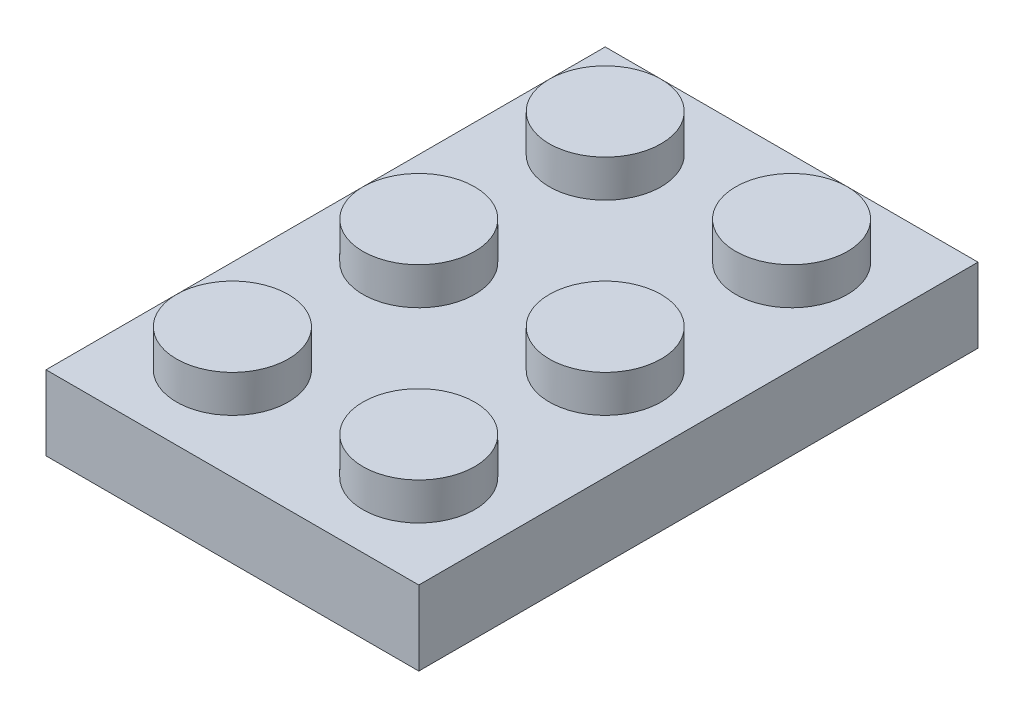
SolidWorks part; units mm, degrees
ref_plane "Front Plane" through (0, 0, 0) normal (0, 0, 1) x (1, 0, 0)
ref_plane "Top Plane" through (0, 0, 0) normal (0, 1, 0) x (1, 0, 0)
ref_plane "Right Plane" through (0, 0, 0) normal (1, 0, 0) x (0, 0, -1)
sketch "Sketch1" plane through (0, 0, 0) normal (0, 1, 0) x (1, 0, 0)
  line L1 (0, 0) -> (16, 0)
  line L2 (0, 0) -> (0, 24)
  line L3 (0, 24) -> (16, 24)
  line L4 (16, 0) -> (16, 24)
  dimension "D1" = 16
  dimension "D2" = 24
extrude "Boss-Extrude1" add sketch "Sketch1" along normal blind 3.2
sketch "Sketch2" plane through (0, 3.2, 0) normal (0, 1, 0) x (1, 0, 0)
  line L0 (8, 0) -> (8, 24) construction
  line L1 (0, 0) -> (16, 0) construction
  line L2 (16, 24) -> (0, 24) construction
  line L3 (16, 0) -> (16, 4) construction
  line L4 (16, 0) -> (16, 24) construction
  line L5 (16, 4) -> (12, 4) construction
  circle A0 centre (12, 4) radius 2.4
  dimension "D3" = 4.8
  dimension "D1" = 4
  dimension "D2" = 4
extrude "Boss-Extrude2" add sketch "Sketch2" along normal blind 1.6
pattern_linear "LPattern1" count 2 spacing 8 along (-1, 0, 0) count 3 spacing 8 along (0, 0, -1) of "Boss-Extrude2"
shell "Shell1" thickness 1.6
